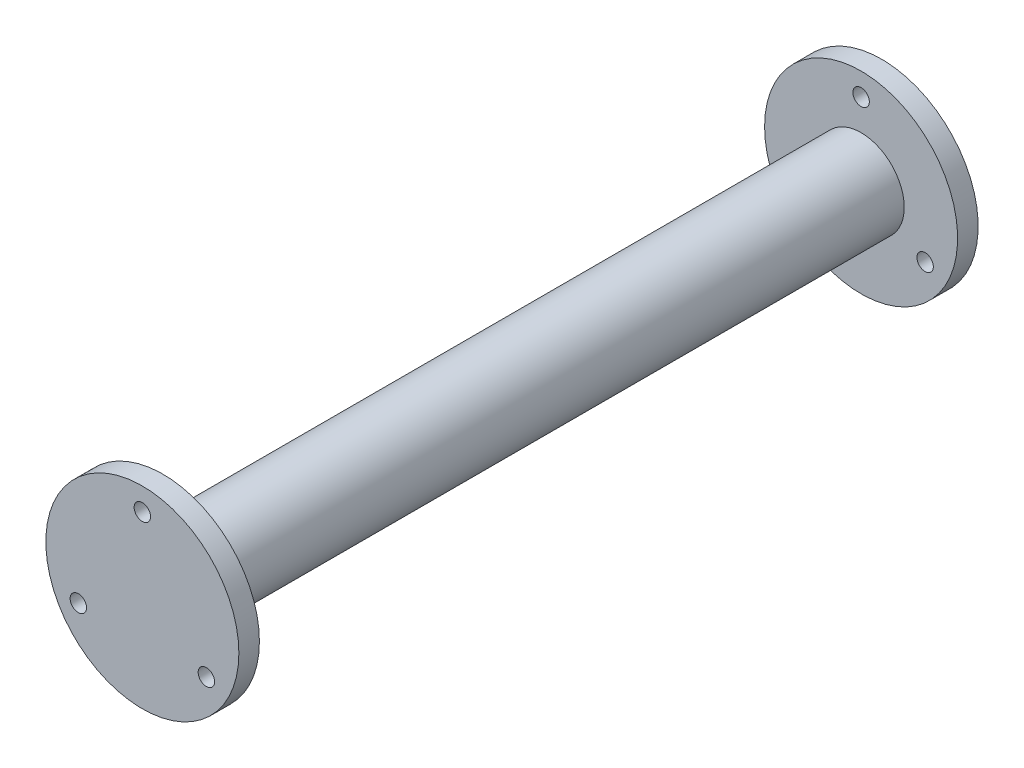
SolidWorks part; units mm, degrees
ref_plane "前视基准面" through (0, 0, 0) normal (0, 0, 1) x (1, 0, 0)
ref_plane "上视基准面" through (0, 0, 0) normal (0, 1, 0) x (1, 0, 0)
ref_plane "右视基准面" through (0, 0, 0) normal (1, 0, 0) x (0, 0, -1)
sketch "草图1" plane through (0, 0, 0) normal (0, 0, 1) x (1, 0, 0)
  circle A0 centre (0, 0) radius 10.5
extrude "凸台-拉伸1" add sketch "草图1" along normal blind 170
sketch "草图2" plane through (0, 0, 170) normal (0, 0, 1) x (1, 0, 0)
  line L0 (0, 0) -> (0, 18) construction
  line L1 (0, 0) -> (15.5885, -9) construction
  line L2 (0, 0) -> (-15.5885, -9) construction
  circle A0 centre (0, 0) radius 23.5
  circle A2 centre (0, 18) radius 2
  circle A3 centre (-15.5885, -9) radius 2
  circle A4 centre (15.5885, -9) radius 2
extrude "凸台-拉伸2" add sketch "草图2" along normal blind 5
sketch "草图3" plane through (0, 0, 0) normal (0, 0, -1) x (-1, 0, 0)
  circle A1 centre (0, 0) radius 23.5
  circle A2 centre (0, 0) radius 23.5
  circle A3 centre (0, 18) radius 2
  circle A4 centre (0, 18) radius 2
  circle A5 centre (15.5885, -9) radius 2
  circle A6 centre (15.5885, -9) radius 2
  circle A7 centre (-15.5885, -9) radius 2
  circle A8 centre (-15.5885, -9) radius 2
  dimension "D1" = 0
  dimension "D2" = 0
  dimension "D3" = 0
  dimension "D4" = 0
extrude "凸台-拉伸3" add sketch "草图3" along normal blind 5
